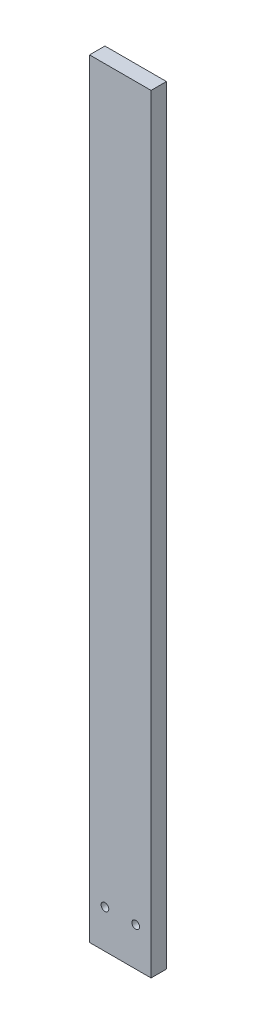
SolidWorks part; units mm, degrees
material "Balsa"
ref_plane "Plan de face" through (0, 0, 0) normal (0, 0, 1) x (1, 0, 0)
ref_plane "Plan de dessus" through (0, 0, 0) normal (0, 1, 0) x (1, 0, 0)
ref_plane "Plan de droite" through (0, 0, 0) normal (1, 0, 0) x (0, 0, -1)
sketch "Sketch1" plane through (0, 0, 0) normal (0, 0, 1) x (1, 0, 0)
  line L1 (-20, -250) -> (20, -250)
  line L2 (-20, -250) -> (-20, 250)
  line L3 (-20, 250) -> (20, 250)
  line L4 (20, -250) -> (20, 250)
  line L5 (-20, -250) -> (20, 250) construction
  line L6 (-20, 250) -> (20, -250) construction
  point P0 (0, 0)
  dimension "D1" = 40
  dimension "D2" = 500
extrude "Boss-Extrude1" add sketch "Sketch1" along normal blind 10
sketch "Sketch2" plane through (0, 0, 0) normal (0, 0, -1) x (-1, 0, 0)
  line L0 (0, 35.0584) -> (0, -130.1565) construction
  line L2 (20, -250) -> (-20, -250) construction
  circle A0 centre (10, -225) radius 2.5
  circle A1 centre (-10, -225) radius 2.5
  dimension "D1" = 5
  dimension "D2" = 10
  dimension "D3" = 25
extrude "Cut-Extrude1" cut sketch "Sketch2" against normal through all
